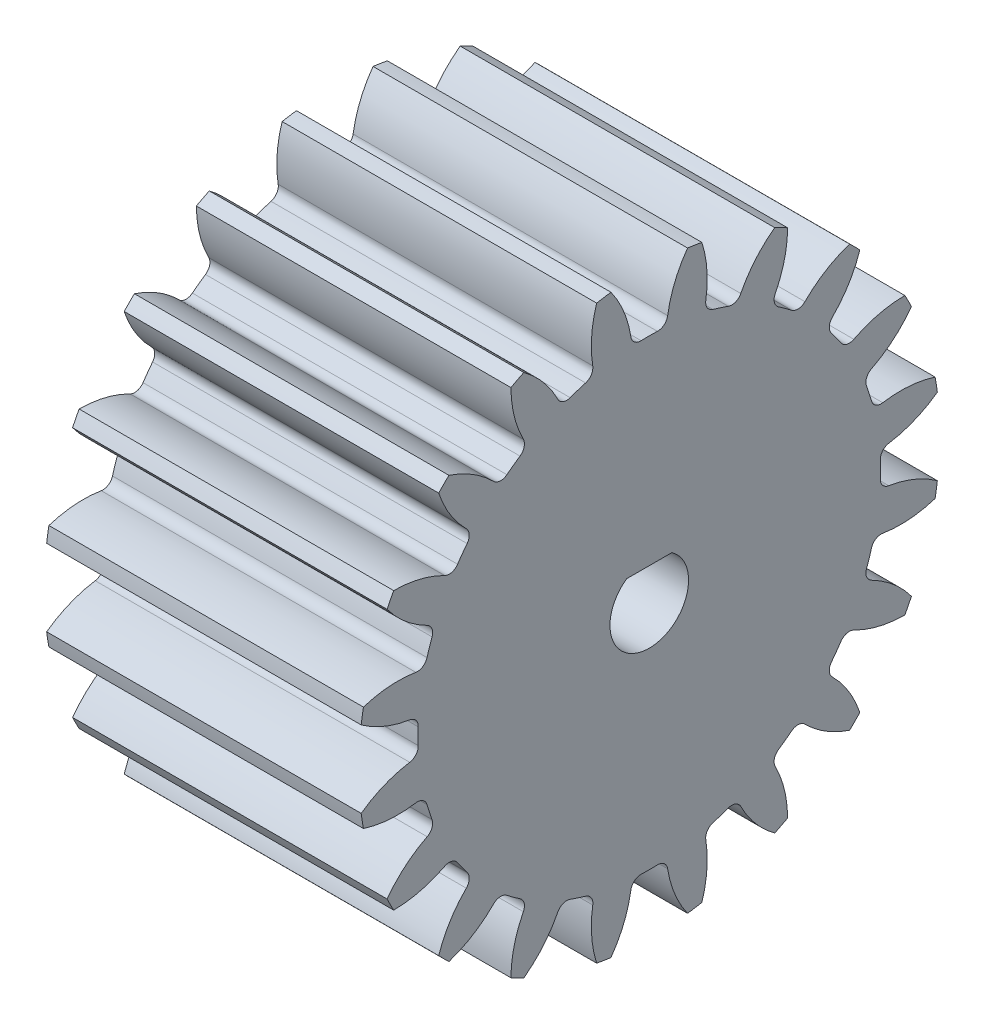
SolidWorks part; units mm, degrees
ref_plane "Front Plane" through (0, 0, 0) normal (0, 0, 1) x (1, 0, 0)
ref_plane "Top Plane" through (0, 0, 0) normal (0, 1, 0) x (1, 0, 0)
ref_plane "Right Plane" through (0, 0, 0) normal (1, 0, 0) x (0, 0, -1)
sketch "Sketch1" plane through (0, 0, 0) normal (1, 0, 0) x (0, 0, -1)
  circle A0 centre (0, 0) radius 3.125
  circle A1 centre (0, 0) radius 23.1
  dimension "D1" = 6.25
  dimension "D2" = 46.2
extrude "Boss-Extrude2" add sketch "Sketch1" along normal blind 25
sketch "Sketch3" plane through (25, 0, 0) normal (1, 0, 0) x (0, 0, -1)
  line L0 (0, 0) -> (0, 23.1) construction
  line L1 (-1.3785, 18.3232) -> (0, 0) construction
  line L2 (0, 15.5171) -> (-1.1841, 18.7704) construction
  circle A0 centre (0, 0) radius 23.1 construction
  arc A1 (1.3785, 18.3232) -> (-1.3785, 18.3232) centre (0, 0) ccw
  arc A2 (1.9643, 20.9079) -> (-1.9643, 20.9079) centre (0, 0) ccw construction
  arc A3 (3.0438, 22.8986) -> (-3.0438, 22.8986) centre (0, 0) ccw
  arc A4 (-3.0438, 22.8986) -> (-1.3785, 18.3232) centre (-10.3511, 17.6482) cw
  arc A5 (3.0438, 22.8986) -> (1.3785, 18.3232) centre (10.3511, 17.6482) ccw
  point P17 (-1.8958, 20.7257)
  dimension "D1" = 46.2
  dimension "D2" = 42
  dimension "D3" = 4.725
  dimension "D4" = 20
  dimension "D5" = 3.9287
extrude "Cut-Extrude1" cut sketch "Sketch3" against normal through all
fillet "Fillet1" radius 0.798 2 edges at (12.5, 18.3232, -1.3785) (12.5, 18.3232, 1.3785)
pattern_circular "CirPattern2" count 20 over 360 about axis through (0, 0, 0) along (1, 0, 0) of "Fillet1", "Cut-Extrude1"
sketch "Sketch4" plane through (0, 0, 0) normal (-1, 0, 0) x (0, 0, 1)
  line L0 (1.2919, -2.8455) -> (3, -2.8455) construction
  line L5 (-1.8, 2.5545) -> (1.8, 2.5545)
  circle A0 centre (0, 0) radius 3.125 construction
  arc A1 (-1.8, 2.5545) -> (1.8, 2.5545) centre (0, 0.1545) cw
  dimension "D2" = 3
  dimension "D1" = 5.4
  dimension "D3" = 3.6
extrude "Boss-Extrude3" add sketch "Sketch4" against normal up to surface (25 mm away) up to face at (25, 0, -3.125)
equation "\"No of teeth\"= 20"
equation "\"Module\" = 2.1"
equation "\"Outer Diameter\"= ( \"No of teeth\" + 2 ) * \"Module\""
equation "\"Pitch Diameter\"= \"No of teeth\" * \"Module\""
equation "\"Backlash\"= 0.3 * \"Module\""
equation "\"Arc Length\"= ( ( \"Module\" * pi ) / 2 ) + \"Backlash\""
equation "\"Fillet Radius\"= 0.38 * \"Module\""
equation "\"Bore Diameter\"= 6.25"
equation "\"Presseure angle\"= 20"
equation "\"Tooth Design\"= IIF ( \"Module\" <= 1.25 , 2.4 * \"Module\" , 2.25 * \"Module\" )"
equation "\"D1@Sketch1\"=\"Bore Diameter\""
equation "\"D2@Sketch1\"=\"Outer Diameter\""
equation "\"D1@Sketch3\"=\"Outer Diameter\""
equation "\"D2@Sketch3\"=\"Pitch Diameter\""
equation "\"D3@Sketch3\"=\"Tooth Design\""
equation "\"D4@Sketch3\"=\"Presseure angle\""
equation "\"D5@Sketch3\"=\"Arc Length\""
equation "\"D1@Fillet1\"=\"Fillet Radius\""
equation "\"D1@CirPattern2\"=\"No of teeth\""
